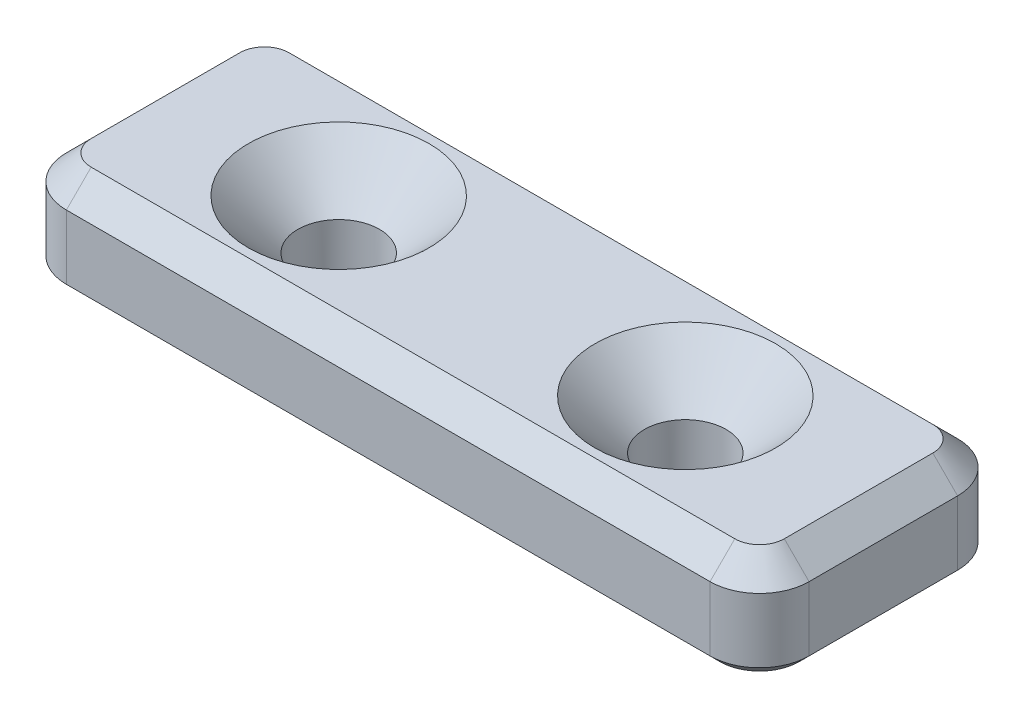
SolidWorks part; units mm, degrees
ref_plane "前视基准面" through (0, 0, 0) normal (0, 0, 1) x (1, 0, 0)
ref_plane "上视基准面" through (0, 0, 0) normal (0, 1, 0) x (1, 0, 0)
ref_plane "右视基准面" through (0, 0, 0) normal (1, 0, 0) x (0, 0, -1)
other "Configuration Table"
sketch "草图1" plane through (0, 0, 0) normal (0, 1, 0) x (1, 0, 0)
  line L1 (0, 0) -> (30, 0)
  line L2 (0, 0) -> (0, 10)
  line L3 (0, 10) -> (30, 10)
  line L4 (30, 0) -> (30, 10)
  dimension "D1" = 10
  dimension "D2" = 30
extrude "凸台-拉伸1" add sketch "草图1" along normal blind 4
sketch "草图2" plane through (0, 4, 0) normal (0, 1, 0) x (1, 0, 0)
  line L0 (0, 10) -> (0, 0) construction
  line L1 (30, 0) -> (30, 10) construction
  circle A0 centre (8, 5) radius 1.65
  circle A1 centre (22, 5) radius 1.65
  dimension "D1" = 8
  dimension "D2" = 3.3
  dimension "D3" = 3.3
  dimension "7" = 8
extrude "切除-拉伸1" cut sketch "草图2" against normal through all
chamfer "倒角1" distance 2 angle 45 2 edges at (22, 4, -3.35) (8, 4, -3.35)
fillet "圆角1" radius 2 4 edges at (30, 2, -10) (30, 2, 0) (0, 2, 0) (0, 2, -10)
chamfer "倒角2" distance 0.4 angle 45 8 edges at (15, 0, 0) (29.4142, 0, -0.5858) (0.5858, 0, -0.5858) (30, 0, -5) (0, 0, -5) (29.4142, 0, -9.4142) (0.5858, 0, -9.4142) (15, 0, -10)
chamfer "倒角3" distance 1 angle 45 8 edges at (15, 4, 0) (29.4142, 4, -0.5858) (0.5858, 4, -0.5858) (30, 4, -5) (0, 4, -5) (29.4142, 4, -9.4142) (0.5858, 4, -9.4142) (15, 4, -10)
